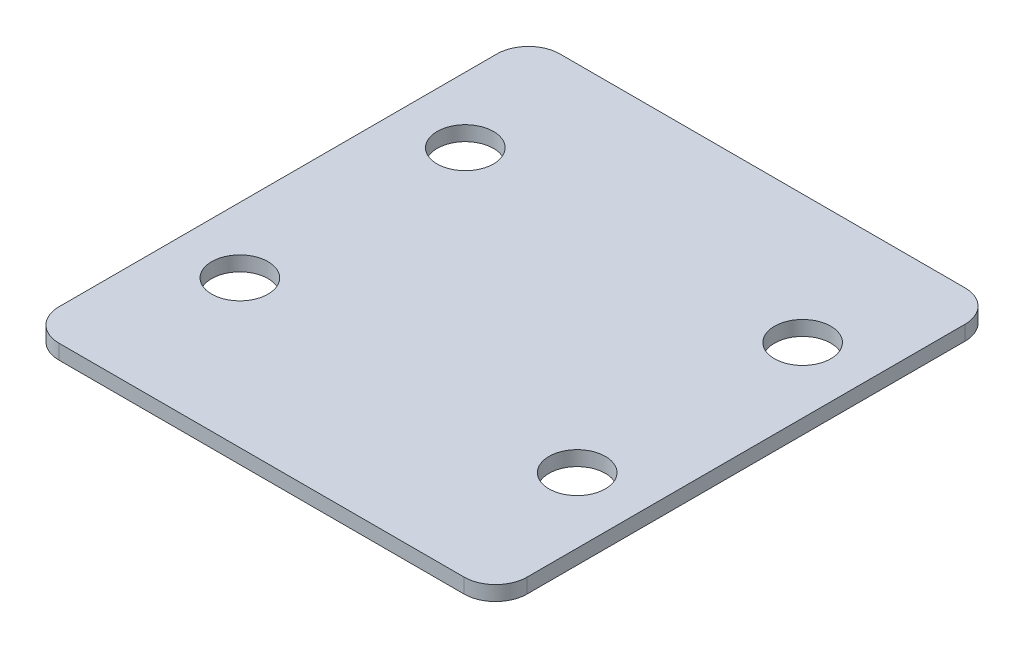
SolidWorks part; units mm, degrees
material "PLA2"
ref_plane "Front Plane" through (0, 0, 0) normal (0, 0, 1) x (1, 0, 0)
ref_plane "Top Plane" through (0, 0, 0) normal (0, 1, 0) x (1, 0, 0)
ref_plane "Right Plane" through (0, 0, 0) normal (1, 0, 0) x (0, 0, -1)
sketch "Sketch1" plane through (0, 0, 0) normal (1, 0, 0) x (0, 0, -1)
  line L0 (0, 0) -> (0, -30.1498)
  line L1 (0, -30.1498) -> (-30.2514, -30.1498)
  line L2 (-30.2514, -30.1498) -> (-30.2514, -29.2608)
  line L3 (-30.2514, -29.2608) -> (-3.1242, -29.2608)
  line L4 (-3.1242, -29.2608) -> (-3.1242, 0)
  line L5 (-3.1242, 0) -> (0, 0)
  dimension "D1" = 30.2514
  dimension "D2" = 30.1498
  dimension "D3" = 3.1242
  dimension "D4" = 0.889
extrude "Boss-Extrude1" add sketch "Sketch1" along normal blind 28.2702
sketch "Sketch2" plane through (0, 0, 3.1242) normal (0, 0, 1) x (1, 0, 0)
  line L0 (14.1351, -3.1496) -> (14.1351, -20.1676) construction
  line L2 (28.2702, 0) -> (0, 0) construction
  line L3 (5.2451, -11.6586) -> (23.0251, -11.6586) construction
  line L6 (0, -11.6586) -> (28.2702, -11.6586) construction
  line L9 (0, 0) -> (0, -29.2608) construction
  line L10 (28.2702, 0) -> (28.2702, -29.2608) construction
  circle A0 centre (14.1351, -11.6586) radius 3.556
  circle A1 centre (14.1351, -3.1496) radius 1.4986
  circle A2 centre (5.2451, -11.6586) radius 2.0066
  circle A3 centre (23.0251, -11.6586) radius 2.0066
  circle A4 centre (14.1351, -20.1676) radius 1.4986
  point P0 (14.1351, -11.6586)
  dimension "D1" = 7.112
  dimension "D2" = 2.9972
  dimension "D3" = 11.6586
  dimension "D7" = 4.0132
  dimension "D4" = 17.78
  dimension "D5" = 17.018
extrude "Motor_Mount_holes" cut sketch "Sketch2" against normal through all
sketch "Sketch3" plane through (0, -29.2608, 0) normal (0, 1, 0) x (1, 0, 0)
  line L0 (14.1351, -3.1242) -> (14.1351, -30.2514) construction
  line L1 (28.2702, -3.1242) -> (0, -3.1242) construction
  line L2 (28.2702, -30.2514) -> (0, -30.2514) construction
  line L3 (28.2702, 0) -> (0, 0) construction
  line L5 (0, -14.5669) -> (28.2702, -14.5669) construction
  circle A0 centre (24.3205, -7.7597) radius 1.7018
  circle A1 centre (3.9497, -7.7597) radius 1.7018
  circle A2 centre (3.9497, -21.3741) radius 1.7018
  circle A3 centre (24.3205, -21.3741) radius 1.7018
  dimension "D1" = 3.4036
  dimension "D2" = 20.3708
  dimension "D3" = 13.6144
  dimension "D4" = 7.7597
extrude "Plate_Mount_Holes" cut sketch "Sketch3" against normal through all
sketch "Sketch4" plane through (0, 0, 3.1242) normal (0, 0, 1) x (1, 0, 0)
  line L4 (0, 0) -> (0, -29.2608)
  line L5 (0, -29.2608) -> (28.2702, -29.2608)
  line L6 (28.2702, -29.2608) -> (28.2702, 0)
  line L7 (28.2702, 0) -> (0, 0)
  line L8 (0, 0) -> (0, -29.2608)
  line L9 (0, -29.2608) -> (28.2702, -29.2608)
  line L10 (28.2702, -29.2608) -> (28.2702, 0)
  line L11 (28.2702, 0) -> (0, 0)
  dimension "D1" = 0
extrude "Cut-Extrude1" cut sketch "Sketch4" against normal through all
fillet "Fillet1" radius 1.905 4 edges at (0, -29.7053, 0) (28.2702, -29.7053, 0) (28.2702, -29.7053, 30.2514) (0, -29.7053, 30.2514)
